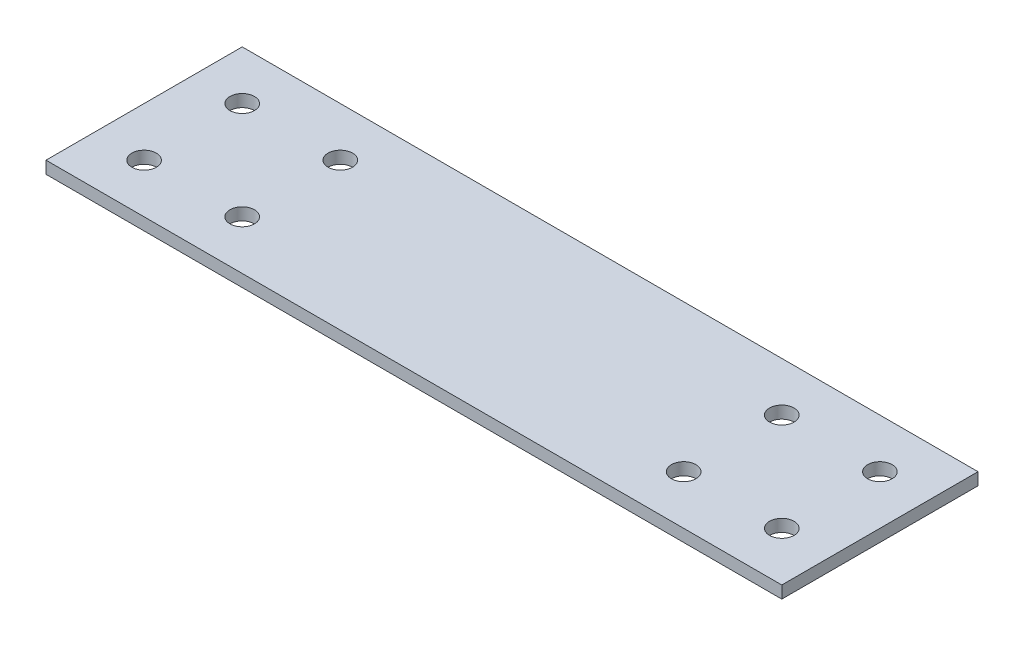
SolidWorks part; units mm, degrees
ref_plane "Front Plane" through (0, 0, 0) normal (0, 0, 1) x (1, 0, 0)
ref_plane "Top Plane" through (0, 0, 0) normal (0, 1, 0) x (1, 0, 0)
ref_plane "Right Plane" through (0, 0, 0) normal (1, 0, 0) x (0, 0, -1)
sketch "Sketch1" plane through (0, 0, 0) normal (0, 1, 0) x (1, 0, 0)
  line L1 (69.85, -25.4) -> (-69.85, -25.4)
  line L2 (69.85, -25.4) -> (69.85, 25.4)
  line L3 (69.85, 25.4) -> (-69.85, 25.4)
  line L4 (-69.85, -25.4) -> (-69.85, 25.4)
  line L5 (69.85, -25.4) -> (-69.85, 25.4) construction
  line L6 (69.85, 25.4) -> (-69.85, -25.4) construction
  point P0 (0, 0)
  dimension "D1" = 50.8
  dimension "D2" = 139.7
extrude "Boss-Extrude1" add sketch "Sketch1" along normal blind 25.4
sketch "Sketch2" plane through (-69.85, 0, 0) normal (-1, 0, 0) x (0, 0, 1)
  line L0 (-25.4, 25.4) -> (-25.4, 0) construction
  line L1 (25.4, 22.225) -> (-25.4, 22.225)
  line L2 (25.4, 22.225) -> (25.4, 0)
  line L3 (25.4, 0) -> (-25.4, 0)
  line L4 (-25.4, 22.225) -> (-25.4, 0)
  line L5 (25.4, 22.225) -> (-25.4, 0) construction
  line L6 (25.4, 0) -> (-25.4, 22.225) construction
  line L7 (25.4, 25.4) -> (25.4, 0) construction
  line L8 (-25.4, 25.4) -> (25.4, 25.4) construction
  line L9 (-25.4, 0) -> (25.4, 0) construction
  point P0 (0, 11.1125)
  dimension "D1" = 0
  dimension "D2" = 0
  dimension "D3" = 3.175
  dimension "D4" = 0
extrude "Cut-Extrude1" cut sketch "Sketch2" against normal up to next
sketch "Sketch3" plane through (0, 25.4, 0) normal (0, 1, 0) x (1, 0, 0)
  line L1 (69.85, 25.4) -> (-69.85, 25.4) construction
  line L2 (-69.85, -25.4) -> (69.85, -25.4) construction
  line L3 (-69.85, 25.4) -> (-69.85, -25.4) construction
  line L4 (-69.85, 0) -> (69.85, 0) construction
  line L5 (69.85, -25.4) -> (69.85, 25.4) construction
  line L6 (0, 25.4) -> (0, -25.4) construction
  circle A0 centre (-57.15, 12.7) radius 3.175
  circle A1 centre (-57.15, -12.7) radius 3.175
  circle A5 centre (57.15, -12.7) radius 3.175
  circle A6 centre (57.15, 12.7) radius 3.175
  dimension "D2" = 6.35
  dimension "D3" = 12.7
  dimension "D4" = 12.7
extrude "Cut-Extrude2" cut sketch "Sketch3" against normal through all
sketch "Sketch5" plane through (-69.85, 0, 0) normal (-1, 0, 0) x (0, 0, 1)
  line L4 (-25.4, 25.4) -> (-25.4, 22.225)
  line L5 (-25.4, 22.225) -> (25.4, 22.225)
  line L6 (25.4, 22.225) -> (25.4, 25.4)
  line L7 (25.4, 25.4) -> (-25.4, 25.4)
  line L8 (-25.4, 25.4) -> (-25.4, 22.225)
  line L9 (-25.4, 22.225) -> (25.4, 22.225)
  line L10 (25.4, 22.225) -> (25.4, 25.4)
  line L11 (25.4, 25.4) -> (-25.4, 25.4)
  dimension "D1" = 0
extrude "Boss-Extrude2" add sketch "Sketch5" along normal blind 25.4
sketch "Sketch7" plane through (69.85, 0, 0) normal (1, 0, 0) x (0, 0, -1)
  line L4 (-25.4, 25.4) -> (-25.4, 22.225)
  line L5 (-25.4, 22.225) -> (25.4, 22.225)
  line L6 (25.4, 22.225) -> (25.4, 25.4)
  line L7 (25.4, 25.4) -> (-25.4, 25.4)
  line L8 (-25.4, 25.4) -> (-25.4, 22.225)
  line L9 (-25.4, 22.225) -> (25.4, 22.225)
  line L10 (25.4, 22.225) -> (25.4, 25.4)
  line L11 (25.4, 25.4) -> (-25.4, 25.4)
  dimension "D1" = 0
extrude "Boss-Extrude3" add sketch "Sketch7" along normal blind 25.4
sketch "Sketch8" plane through (0, 25.4, 0) normal (0, 1, 0) x (1, 0, 0)
  line L0 (-69.85, -25.4) -> (-69.85, 25.4) construction
  line L1 (-95.25, -25.4) -> (95.25, -25.4) construction
  line L2 (95.25, 25.4) -> (-95.25, 25.4) construction
  line L3 (69.85, 25.4) -> (69.85, -25.4) construction
  line L4 (-95.25, -25.4) -> (-95.25, 25.4) construction
  line L5 (95.25, 25.4) -> (95.25, -25.4) construction
  line L6 (-95.25, 0) -> (95.25, 0) construction
  line L7 (0, 25.4) -> (0, -25.4) construction
  circle A0 centre (-82.55, 12.7) radius 3.175
  circle A1 centre (-82.55, -12.7) radius 3.175
  circle A2 centre (82.55, -12.7) radius 3.175
  circle A3 centre (82.55, 12.7) radius 3.175
  dimension "D3" = 6.35
  dimension "D4" = 12.7
  dimension "D5" = 12.7
  dimension "D1" = 25.4
  dimension "D2" = 25.4
extrude "Cut-Extrude3" cut sketch "Sketch8" against normal up to next
